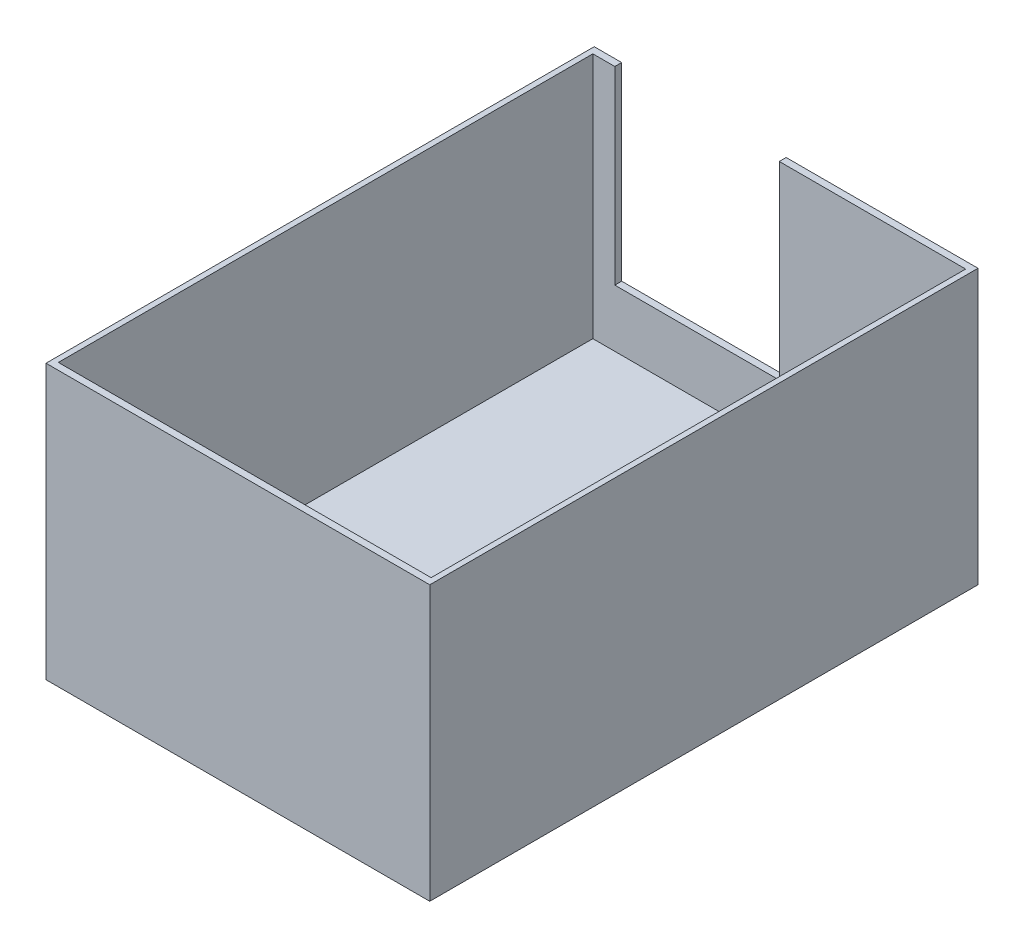
SolidWorks part; units mm, degrees
ref_plane "Front Plane" through (0, 0, 0) normal (0, 0, 1) x (1, 0, 0)
ref_plane "Top Plane" through (0, 0, 0) normal (0, 1, 0) x (1, 0, 0)
ref_plane "Right Plane" through (0, 0, 0) normal (1, 0, 0) x (0, 0, -1)
sketch "Sketch1" plane through (0, 0, 0) normal (0, 1, 0) x (1, 0, 0)
  line L1 (-35, 50) -> (35, 50)
  line L2 (-35, 50) -> (-35, -50)
  line L3 (-35, -50) -> (35, -50)
  line L4 (35, 50) -> (35, -50)
  line L5 (-35, 50) -> (35, -50) construction
  line L6 (-35, -50) -> (35, 50) construction
  point P0 (0, 0)
  dimension "D1" = 70
  dimension "D2" = 100
extrude "Boss-Extrude1" add sketch "Sketch1" along normal blind 50
sketch "Sketch3" plane through (0, 50, 0) normal (0, 1, 0) x (1, 0, 0)
  line L1 (-34, 48.75) -> (34, 48.75)
  line L2 (-34, 48.75) -> (-34, -48.75)
  line L3 (-34, -48.75) -> (34, -48.75)
  line L4 (34, 48.75) -> (34, -48.75)
  line L5 (-34, 48.75) -> (34, -48.75) construction
  line L6 (-34, -48.75) -> (34, 48.75) construction
  point P0 (0, 0)
  dimension "D1" = 97.5
  dimension "D2" = 68
extrude "Cut-Extrude1" cut sketch "Sketch3" against normal blind 45
sketch "Sketch5" plane through (0, 0, -50) normal (0, 0, -1) x (-1, 0, 0)
  line L1 (0, 15.4616) -> (30, 15.4616)
  line L2 (0, 15.4616) -> (0, 55.4616)
  line L3 (0, 55.4616) -> (30, 55.4616)
  line L4 (30, 15.4616) -> (30, 55.4616)
  dimension "D1" = 40
  dimension "D2" = 30
extrude "Cut-Extrude2" cut sketch "Sketch5" against normal blind 5.5
